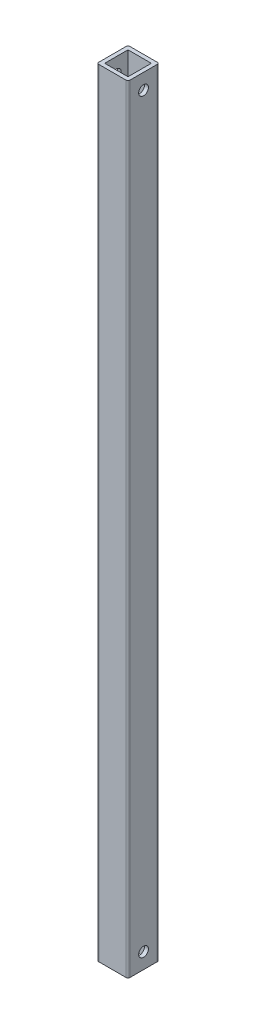
SolidWorks part; units mm, degrees
ref_plane "Front Plane" through (0, 0, 0) normal (0, 0, 1) x (1, 0, 0)
ref_plane "Top Plane" through (0, 0, 0) normal (0, 1, 0) x (1, 0, 0)
ref_plane "Right Plane" through (0, 0, 0) normal (1, 0, 0) x (0, 0, -1)
sketch "Sketch1" plane through (0, 0, 0) normal (0, 1, 0) x (1, 0, 0)
  line L0 (-1.1481, 6.9259) -> (-1.1481, -5.0741)
  line L1 (-3.1481, 8.9259) -> (12.8519, 8.9259)
  line L2 (-3.1481, 8.9259) -> (-3.1481, -7.0741)
  line L3 (-3.1481, -7.0741) -> (12.8519, -7.0741)
  line L4 (12.8519, 8.9259) -> (12.8519, -7.0741)
  line L5 (-1.1481, -5.0741) -> (10.8519, -5.0741)
  line L6 (10.8519, 6.9259) -> (10.8519, -5.0741)
  line L7 (-1.1481, 6.9259) -> (10.8519, 6.9259)
  dimension "D1" = 16
  dimension "D2" = 16
  dimension "D3" = 2
extrude "Boss-Extrude1" add sketch "Sketch1" along normal blind 400
fillet "Fillet2" radius 1 4 edges at (12.8519, 200, -8.9259) (-3.1481, 200, -8.9259) (12.8519, 200, 7.0741) (-3.1481, 200, 7.0741)
sketch "Sketch2" plane through (-3.1481, 0, 0) normal (-1, 0, 0) x (0, 0, 1)
  line L0 (7.0741, 400) -> (7.0741, 0) construction
  line L1 (-7.9259, 0) -> (6.0741, 0) construction
  line L2 (-7.9259, 400) -> (6.0741, 400) construction
  line L3 (-8.9259, 0) -> (-8.9259, 400) construction
  circle A0 centre (-0.9259, 8) radius 2.5
  circle A1 centre (-0.9259, 392) radius 2.5
  dimension "D1" = 5
  dimension "D6" = 5
  dimension "D2" = 8
  dimension "D3" = 8
  dimension "D4" = 8
  dimension "D5" = 8
extrude "Cut-Extrude1" cut sketch "Sketch2" against normal blind 16
